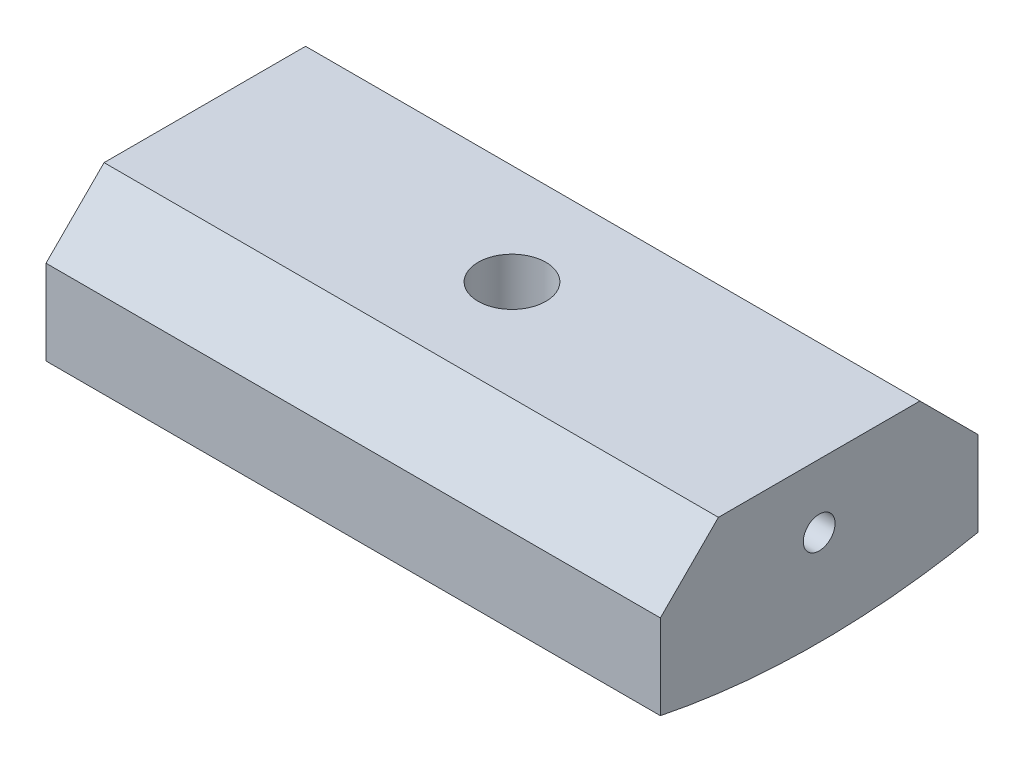
SolidWorks part; units mm, degrees
material "Beech"
ref_plane "Front Plane" through (0, 0, 0) normal (0, 0, 1) x (1, 0, 0)
ref_plane "Top Plane" through (0, 0, 0) normal (0, 1, 0) x (1, 0, 0)
ref_plane "Right Plane" through (0, 0, 0) normal (1, 0, 0) x (0, 0, -1)
sketch "Sketch1" plane through (0, 0, 0) normal (1, 0, 0) x (0, 0, -1)
  line L0 (0, 0) -> (0, -90.5205) construction
  line L1 (-15, -60) -> (15, -60) construction
  line L2 (-15, -60) -> (-15, -73.4847) construction
  line L3 (15, -73.4847) -> (15, -65.4847)
  line L4 (15, -60) -> (15, -73.4847) construction
  line L5 (15, -65.4847) -> (9.5153, -60)
  line L6 (9.5153, -60) -> (0, -60)
  line L7 (0, -60) -> (-9.5153, -60)
  line L8 (-9.5153, -60) -> (-15, -65.4847)
  line L9 (-15, -65.4847) -> (-15, -73.4847)
  arc A0 (-15, -73.4847) -> (15, -73.4847) centre (0, 0) ccw construction
  arc A1 (-15, -73.4847) -> (15, -73.4847) centre (0, 0) ccw
  circle A2 centre (0, 0) radius 75 construction
  point P7 (0, -75)
  dimension "D1" = 150
  dimension "D2" = 15
  dimension "D3" = 30
  dimension "D5" = 8
  dimension "D4" = 45
extrude "Boss-Extrude1" add sketch "Sketch1" along normal blind 58.024
sketch "Sketch2" plane through (0, -60, 0) normal (0, 1, 0) x (1, 0, 0)
  line L0 (0, 9.5153) -> (58.024, -9.5153) construction
  line L1 (0, -9.5153) -> (58.024, 9.5153) construction
  line L2 (58.024, 9.5153) -> (0, 9.5153) construction
  circle A0 centre (29.012, 0) radius 3.2
  dimension "D1" = 6.4
extrude "Cut-Extrude1" cut sketch "Sketch2" against normal through all
sketch "Sketch4" plane through (0, 0, 0) normal (1, 0, 0) x (0, 0, -1)
  line L0 (0, 0) -> (0, -66) construction
  circle A0 centre (0, -66) radius 1.5
  dimension "D2" = 3
  dimension "D1" = 66
extrude "Cut-Extrude2" cut sketch "Sketch4" along normal blind 5
sketch "Sketch5" plane through (58.024, 0, 0) normal (1, 0, 0) x (0, 0, -1)
  line L0 (0, 0) -> (0, -66) construction
  circle A0 centre (0, -66) radius 1.5
  dimension "D2" = 3
  dimension "D1" = 66
extrude "Cut-Extrude4" cut sketch "Sketch5" against normal blind 5
equation "\"d_i_tube\"= 150mm'Inner Rocket Body Composite Tube Diameter"
equation "\"t_tube\"= 1.182mm'Thickness of Rocket Body Composite Tube"
equation "\"l_upper_body_tube\"= 949.3mm'Upper Rocket Body Composite Tube length"
equation "\"l_lower_body_tube\"= 816mm'Lower Rocket Body Composite Tube Length"
equation "\"d_a_NC\"= 154mm'Outer Diameter of Nosecone base"
equation "\"d_i_phenolic_tube\"= 152.3mm'Inner Phenolic Tube Diameter"
equation "\"t_phenolic_tube\"= 2mm'Thickness of Phenolic Body Tube"
equation "\"l_fin_cut\"= 220mm'Length of fin on Motor Retainer"
equation "\"t_SW-Panel\"= 11.482mm'Thickness of Sandwich-Panel"
equation "\"l_motor_tube\"=610mm'Length of phenolic motor tube"
equation "\"d_i_motor_tube\"=99.06mm'Inner diameter of phenolic motor tube"
equation "\"t_motor_tube\"=1.58mm'Thicknes of phenolic motor tube"
equation "\"l_cut_fin_centering\"=13mm'Length of cut for fin alignement on fin centering rings"
equation "\"D1@Sketch1\"=\"d_i_tube\""
equation "\"D1@Boss-Extrude1\"=(\"l_fin_cut\"-(\"t_SW-Panel\"*4))/3"
